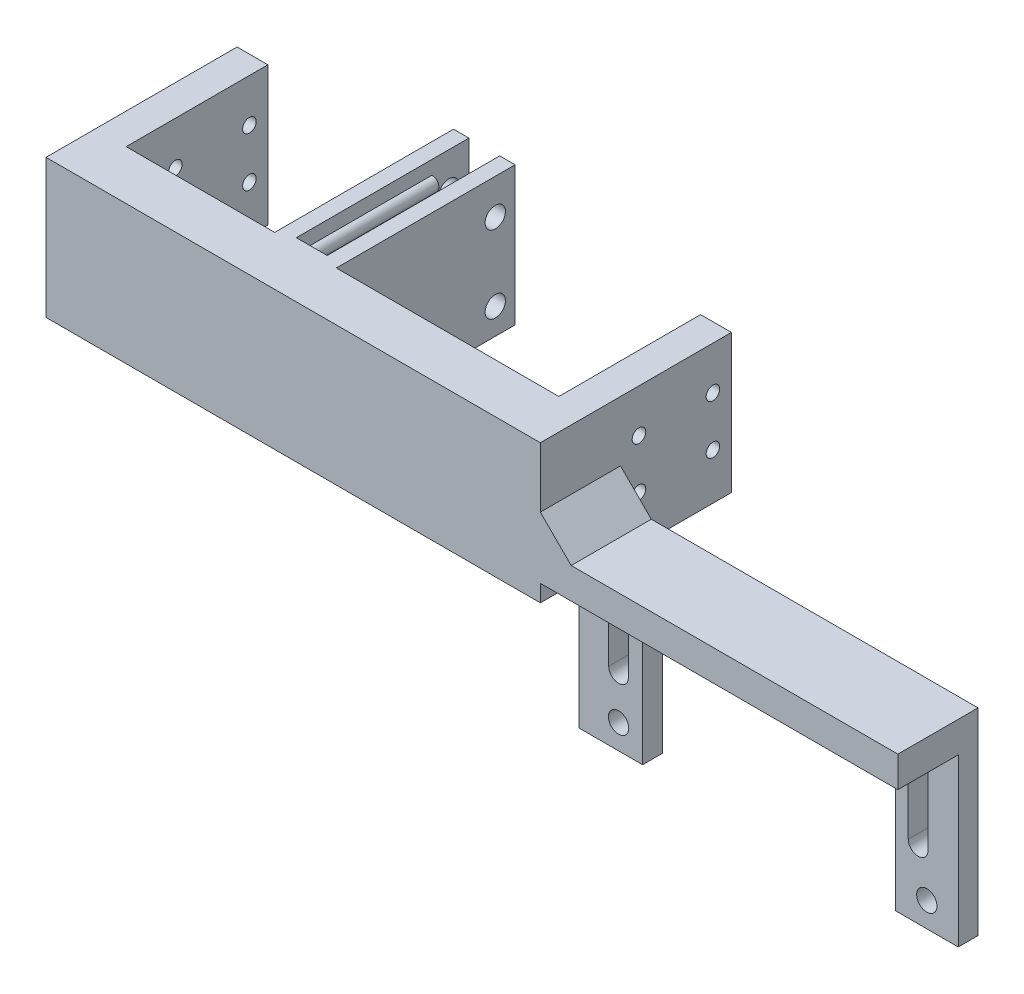
SolidWorks part; units mm, degrees
ref_plane "前视基准面" through (0, 0, 0) normal (0, 0, 1) x (1, 0, 0)
ref_plane "上视基准面" through (0, 0, 0) normal (0, 1, 0) x (1, 0, 0)
ref_plane "右视基准面" through (0, 0, 0) normal (1, 0, 0) x (0, 0, -1)
other "Configuration Table"
sketch "草图1" plane through (0, 0, 0) normal (0, 1, 0) x (1, 0, 0)
  line L0 (-35.1, 11.5) -> (-40.1, 11.5)
  line L1 (-35.1, 11.5) -> (35.1, 11.5)
  line L2 (-35.1, 11.5) -> (-35.1, -11.5)
  line L3 (-35.1, -11.5) -> (35.1, -11.5)
  line L4 (35.1, 11.5) -> (35.1, -11.5)
  line L5 (-35.1, 11.5) -> (35.1, -11.5) construction
  line L6 (-35.1, -11.5) -> (35.1, 11.5) construction
  line L7 (-40.1, 11.5) -> (-40.1, -19.5)
  line L8 (-40.1, -19.5) -> (40.1, -19.5)
  line L9 (40.1, -19.5) -> (40.1, 11.5)
  line L10 (40.1, 11.5) -> (35.1, 11.5)
  point P0 (0, 0)
  dimension "D1" = 70.2
  dimension "D2" = 5
  dimension "D3" = 5
  dimension "D4" = 8
  dimension "D5" = 23
extrude "凸台-拉伸1" add sketch "草图1" along normal blind 22.5 contours L9 L10 L4 L3 L2 L0 L7 L8
sketch "草图2" plane through (-40.1, 0, 0) normal (-1, 0, 0) x (0, 0, 1)
  line L0 (-15.7741, 11.5) -> (24.018, 11.5) construction
  line L1 (-11.5, 22.5) -> (-11.5, 0) construction
  line L2 (-11.5, 22.5) -> (19.5, 22.5) construction
  line L3 (-2.5, 20.343) -> (-2.5, 14.7795) construction
  circle A0 centre (-8.5, 15.5) radius 1.1
  circle A1 centre (3.5, 15.5) radius 1.1
  circle A4 centre (3.5, 7.5) radius 1.1
  circle A5 centre (-8.5, 7.5) radius 1.1
  dimension "D1" = 2.2
  dimension "D2" = 7
  dimension "D3" = 3
  dimension "D4" = 6
  dimension "D5" = 4
extrude "切除-拉伸1" cut sketch "草图2" against normal blind 117 and the other way blind 55
sketch "草图3" plane through (0, 22.5, 0) normal (0, 1, 0) x (1, 0, 0)
  line L1 (-11.5, -12.5) -> (-1.5, -12.5)
  line L2 (-11.5, -12.5) -> (-11.5, 12.599)
  line L3 (-11.5, 12.599) -> (-1.5, 12.599)
  line L4 (-1.5, -12.5) -> (-1.5, 12.599)
  line L5 (-7.5, -4.4885) -> (-7.5, 11.5115) construction
  line L6 (-8, 11.5115) -> (8, 11.5115) construction
  line L7 (-6.5, 12.599) -> (-6.5, -12.5) construction
  dimension "D1" = 10
  dimension "D2" = 1
extrude "凸台-拉伸2" [suppressed] add sketch "草图3" against normal up to surface (22.5 mm away)
sketch "草图4" plane through (-40.1, 0, 0) normal (-1, 0, 0) x (0, 0, 1)
  line L0 (-10.8, -17.25) -> (9.2, -17.25) construction
  line L1 (19.5, 22.5) -> (9.5, 22.5)
  line L2 (19.5, 22.5) -> (19.5, -17.25)
  line L3 (19.5, -17.25) -> (9.5, -17.25)
  line L4 (9.5, 22.5) -> (9.5, -17.25)
  dimension "D1" = 10
extrude "凸台-拉伸3" [suppressed] add sketch "草图4" along normal blind 55
sketch "草图5" plane through (40.1, 0, 0) normal (1, 0, 0) x (0, 0, -1)
  line L0 (-9.2, 2.75) -> (10.8, 2.75) construction
  line L1 (-6.5, 2.75) -> (-19.5, 2.75)
  line L2 (-6.5, 2.75) -> (-6.5, 7.75)
  line L3 (-6.5, 7.75) -> (-19.5, 7.75)
  line L4 (-19.5, 2.75) -> (-19.5, 7.75)
  line L5 (-19.5, 22.5) -> (-19.5, 0) construction
  circle A0 centre (-3.5, 7.5) radius 1.1 construction
  dimension "D1" = 5
  dimension "D2" = 3
extrude "凸台-拉伸4" add sketch "草图5" along normal blind 58
chamfer "倒角1" distance 5 angle 45 1 edges at (40.1, 7.75, 13)
sketch "草图6" plane through (0, 2.75, 0) normal (0, -1, 0) x (1, 0, 0)
  line L0 (46.888, 9.2) -> (46.888, 17.85) construction
  line L1 (46.888, 9.7) -> (36.6006, 9.7)
  line L2 (46.888, 9.7) -> (46.888, 6.5)
  line L3 (46.888, 6.5) -> (36.6006, 6.5)
  line L4 (36.6006, 9.7) -> (36.6006, 6.5)
  line L5 (42.288, 9.7) -> (46.888, 9.7) construction
  line L7 (87.888, 9.7) -> (98.1, 9.7)
  line L8 (87.888, 9.7) -> (87.888, 6.5)
  line L9 (87.888, 6.5) -> (98.1, 6.5)
  line L10 (98.1, 9.7) -> (98.1, 6.5)
extrude "凸台-拉伸5" add sketch "草图6" along normal blind 27
sketch "草图7" plane through (0, 0, 9.7) normal (0, 0, 1) x (1, 0, 0)
  line L0 (91.583, -13.1622) -> (91.583, -0.1622) construction
  line L1 (89.983, -13.1622) -> (89.983, -0.1622)
  line L2 (93.183, -13.1622) -> (93.183, -0.1622)
  line L3 (42.988, -13.1622) -> (42.988, -0.1622) construction
  line L4 (41.388, -13.1622) -> (41.388, -0.1622)
  line L5 (44.588, -13.1622) -> (44.588, -0.1622)
  arc A0 (89.983, -13.1622) -> (93.183, -13.1622) centre (91.583, -13.1622) ccw
  arc A1 (93.183, -0.1622) -> (89.983, -0.1622) centre (91.583, -0.1622) ccw
  arc A2 (41.388, -13.1622) -> (44.588, -13.1622) centre (42.988, -13.1622) ccw
  arc A3 (44.588, -0.1622) -> (41.388, -0.1622) centre (42.988, -0.1622) ccw
  point P2 (91.583, -6.6622)
  point P10 (42.988, -6.6622)
  dimension "D1" = 1.6
  dimension "D2" = 1.6
  dimension "D3" = 13
  dimension "D4" = 13
extrude "切除-拉伸2" cut sketch "草图7" against normal blind 27
sketch "草图8" plane through (0, 0, 9.7) normal (0, 0, 1) x (1, 0, 0)
  line L2 (92.994, -24.25) -> (92.994, -20.25) construction
  line L3 (98.1, -24.25) -> (87.888, -24.25) construction
  circle A0 centre (92.994, -20.25) radius 1.65
  circle A1 centre (42.994, -20.25) radius 1.65
  point P2 (0, 0)
  dimension "D1" = 3.3
  dimension "D2" = 3.3
  dimension "D3" = 50
  dimension "D4" = 4
extrude "切除-拉伸3" cut sketch "草图8" against normal blind 27
sketch "草图10" plane through (0, 0, 11.5) normal (0, 0, -1) x (-1, 0, 0)
  circle A0 centre (-4.65, 2.5) radius 1.6
  circle A1 centre (-20.65, 2.5) radius 1.6
  circle A2 centre (-20.65, 17.5) radius 1.6
  circle A3 centre (-4.65, 17.5) radius 1.6
  dimension "D1" = 3.2
extrude "切除-拉伸4" [suppressed] cut sketch "草图10" against normal blind 25
sketch "草图11" plane through (0, 0, 0) normal (0, -1, 0) x (1, 0, 0)
  line L0 (-35.1, 11.5) -> (35.1, 11.5) construction
  line L1 (-11, 11.5) -> (-1, 11.5)
  line L2 (-11, 11.5) -> (-11, -11.5115)
  line L3 (-11, -11.5115) -> (-1, -11.5115)
  line L4 (-1, 11.5) -> (-1, -11.5115)
  line L5 (6, -11.5115) -> (-6, -11.5115) construction
  line L6 (-6, 11.5) -> (-6, 1.9447) construction
  line L7 (-6, 4.4885) -> (-6, -11.5115) construction
  dimension "D1" = 10
extrude "凸台-拉伸6" add sketch "草图11" against normal up to surface (22.5 mm away) up to face at (0, 22.5, 2)
sketch "草图12" plane through (0, 0, -11.5115) normal (0, 0, -1) x (-1, 0, 0)
  line L0 (6, 0) -> (6, 22.5) construction
  line L1 (11, 0) -> (1, 0) construction
  line L2 (11, 22.5) -> (1, 22.5) construction
  line L4 (8.5, 0) -> (3.5, 0)
  line L5 (8.5, 0) -> (8.5, 22.5)
  line L6 (8.5, 22.5) -> (3.5, 22.5)
  line L7 (3.5, 0) -> (3.5, 22.5)
  dimension "D1" = 5
extrude "切除-拉伸5" cut sketch "草图12" against normal blind 22
sketch "草图14" plane through (0, 0, -11.5115) normal (0, 0, -1) x (-1, 0, 0)
  line L0 (8.5, 0) -> (8.5, 22.5) construction
  line L1 (8.5, 0) -> (8.5, 20.277)
  arc A0 (8.5, 0) -> (8.5, 2.277) centre (8.5, 1.1385) cw
  arc A1 (8.5, 3) -> (8.5, 5.277) centre (8.5, 4.1385) cw
  arc A2 (8.5, 6) -> (8.5, 8.277) centre (8.5, 7.1385) cw
  arc A3 (8.5, 9) -> (8.5, 11.277) centre (8.5, 10.1385) cw
  arc A4 (8.5, 12) -> (8.5, 14.277) centre (8.5, 13.1385) cw
  arc A5 (8.5, 15) -> (8.5, 17.277) centre (8.5, 16.1385) cw
  arc A6 (8.5, 18) -> (8.5, 20.277) centre (8.5, 19.1385) cw
  line M4 (8.5, 22.5) -> (8.5, 0)
  dimension "D1" = 7
extrude "凸台-拉伸8" add sketch "草图14" against normal blind 22 contours A0 L1 | A1 L1 | A2 L1 | A3 L1 | A5 L1 | A6 M4 | A4 L1
sketch "草图15" plane through (0, 0, -11.5115) normal (0, 0, -1) x (-1, 0, 0)
  line L0 (11, 0) -> (8.5, 0) construction
  line L1 (8.5, 0) -> (3.5, 0)
  line L2 (8.5, 0) -> (8.5, 22.5)
  line L3 (8.5, 22.5) -> (3.5, 22.5)
  line L4 (3.5, 0) -> (3.5, 22.5)
  arc A0 (8.5, 2.277) -> (8.5, 0) centre (8.5, 1.1385) ccw construction
extrude "切除-拉伸6" [suppressed] cut sketch "草图15" against normal blind 6
sketch "草图16" plane through (0, 0, -11.5115) normal (0, 0, -1) x (-1, 0, 0)
  line L1 (11, 0) -> (8.5, 0)
  line L2 (11, 0) -> (11, 22.5)
  line L3 (11, 22.5) -> (8.5, 22.5)
  line L4 (8.5, 0) -> (8.5, 22.5)
  line L5 (3.5, 0) -> (1, 0)
  line L6 (3.5, 0) -> (3.5, 22.5)
  line L7 (3.5, 22.5) -> (1, 22.5)
  line L8 (1, 0) -> (1, 22.5)
extrude "凸台-拉伸9" add sketch "草图16" along normal blind 6
sketch "草图17" plane through (-11, 0, 0) normal (-1, 0, 0) x (0, 0, 1)
  circle A0 centre (-14.2891, 4.226) radius 1.65
  circle A1 centre (-14.2891, 16.7479) radius 1.65
  dimension "D1" = 3.3
extrude "切除-拉伸7" cut sketch "草图17" against normal blind 14
